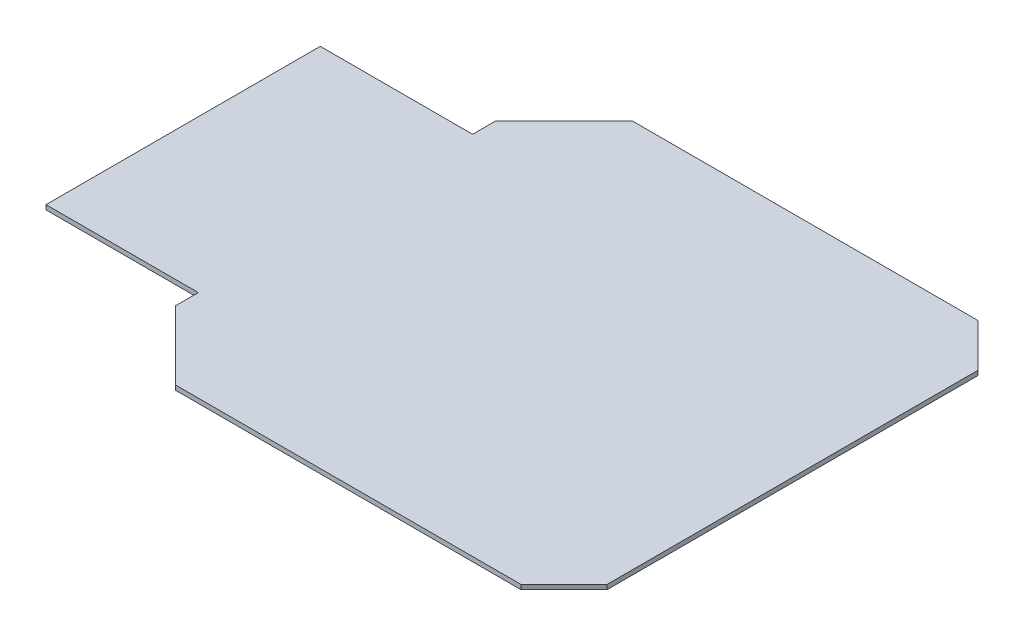
SolidWorks part; units mm, degrees
material "1023 Carbon Steel Sheet (SS)"
ref_plane "Front Plane" through (0, 0, 0) normal (0, 0, 1) x (1, 0, 0)
ref_plane "Top Plane" through (0, 0, 0) normal (0, 1, 0) x (1, 0, 0)
ref_plane "Right Plane" through (0, 0, 0) normal (1, 0, 0) x (0, 0, -1)
sketch "Sketch1" plane through (0, 0, 0) normal (0, 1, 0) x (1, 0, 0)
  line L0 (-245.1836, 942.3231) -> (-245.1836, 742.3231)
  line L1 (-245.1836, 742.3231) -> (-145.1836, 692.3231)
  line L2 (-145.1836, 692.3231) -> (126.5321, 692.3231)
  line L3 (126.5321, 692.3231) -> (154.8164, 720.6074)
  line L4 (154.8164, 720.6074) -> (154.8164, 964.0388)
  line L6 (126.5321, 992.3231) -> (-145.1836, 992.3231)
  line L7 (-145.1836, 992.3231) -> (-245.1836, 942.3231)
  line L8 (126.5321, 992.3231) -> (154.8164, 964.0388)
  point P2 (154.8164, 842.3231)
  point P9 (-245.1836, 842.3231)
  dimension "D1" = 300
  dimension "D2" = 400
  dimension "D3" = 200
  dimension "D4" = 150
  dimension "D5" = 100
  dimension "D6" = 45
  dimension "D7" = 150
  dimension "D8" = 0
  dimension "D9" = 45
  dimension "D10" = 40
extrude "Boss-Extrude1" add sketch "Sketch1" along normal blind 3 contours L6 L7 L0 L1 L2 L3 L4 L8
sketch "Sketch3" plane through (0, 3, 0) normal (0, 1, 0) x (1, 0, 0)
  line L0 (-154.8988, 932.3231) -> (-247.0462, 932.3231) construction
  line L1 (-145.1836, 1023.2901) -> (-247.5584, 1023.2901)
  line L2 (-145.1836, 1023.2901) -> (-145.1836, 932.3231)
  line L3 (-145.1836, 932.3231) -> (-247.5584, 932.3231)
  line L4 (-247.5584, 1023.2901) -> (-247.5584, 932.3231)
  line L5 (-145.1836, 682.3796) -> (-298.8324, 682.3796)
  line L6 (-145.1836, 682.3796) -> (-145.1836, 752.3231)
  line L7 (-145.1836, 752.3231) -> (-298.8324, 752.3231)
  line L8 (-298.8324, 682.3796) -> (-298.8324, 752.3231)
  line L9 (-247.0462, 752.3231) -> (-154.8988, 752.3231) construction
  dimension "D1" = 0
  dimension "D2" = 0
  dimension "D3" = 0
  dimension "D4" = 0
extrude "Cut-Extrude2" cut sketch "Sketch3" against normal blind 10
sketch "Sketch4" plane through (0, 3, 0) normal (0, 1, 0) x (1, 0, 0)
  line L0 (-145.1836, 947.3231) -> (-100.1836, 992.3231)
  line L1 (-145.1836, 932.3231) -> (-145.1836, 992.3231) construction
  line L2 (126.5321, 992.3231) -> (-145.1836, 992.3231) construction
  line L3 (-100.1836, 992.3231) -> (-145.1836, 992.3231)
  line L4 (-145.1836, 992.3231) -> (-145.1836, 947.3231)
  line L5 (-100.1836, 692.3231) -> (-145.1836, 692.3231)
  line L6 (-145.1836, 692.3231) -> (126.5321, 692.3231) construction
  line L7 (-145.1836, 692.3231) -> (-145.1836, 737.3231)
  line L8 (-145.1836, 692.3231) -> (-145.1836, 752.3231) construction
  line L9 (-145.1836, 737.3231) -> (-100.1836, 692.3231)
  dimension "D1" = 45
  dimension "D2" = 45
  dimension "D3" = 45
  dimension "D4" = 45
extrude "Cut-Extrude3" cut sketch "Sketch4" against normal blind 60
